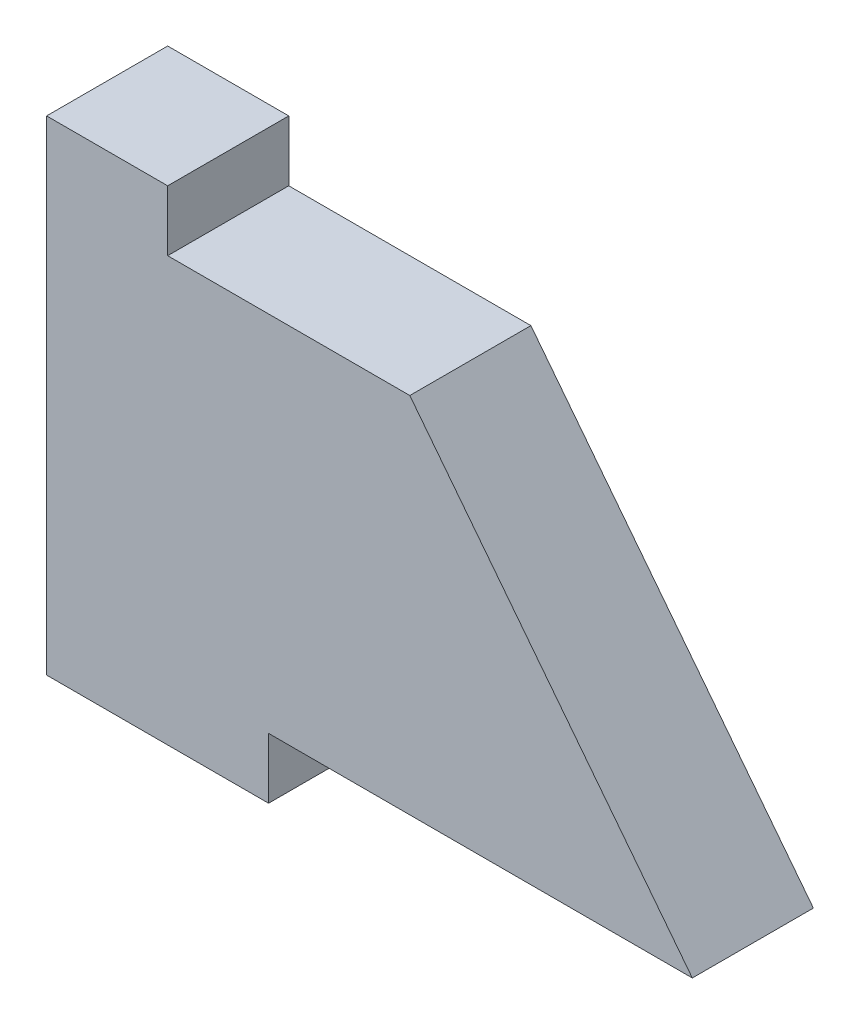
SolidWorks part; units mm, degrees
ref_plane "Спереди" through (0, 0, 0) normal (0, 0, 1) x (1, 0, 0)
ref_plane "Сверху" through (0, 0, 0) normal (0, 1, 0) x (1, 0, 0)
ref_plane "Справа" through (0, 0, 0) normal (1, 0, 0) x (0, 0, -1)
sketch "Эскиз1" plane through (0, 0, 0) normal (0, 0, 1) x (1, 0, 0)
  line L0 (0, 9) -> (0, 0)
  line L1 (0, 0) -> (16, 0)
  line L2 (16, 0) -> (9, 9)
  line L3 (9, 9) -> (0, 9)
  dimension "D1" = 9
  dimension "D2" = 9
  dimension "D3" = 16
extrude "Бобышка-Вытянуть1" add sketch "Эскиз1" along normal blind 3
sketch "Эскиз2" plane through (0, 9, 0) normal (0, 1, 0) x (1, 0, 0)
  line L0 (0, -3) -> (0, 0) construction
  line L1 (0, 0) -> (3, 0)
  line L2 (0, 0) -> (0, -3)
  line L3 (0, -3) -> (3, -3)
  line L4 (3, 0) -> (3, -3)
  line L7 (9, -3) -> (0, -3) construction
  line L8 (9, 0) -> (0, 0) construction
  point P6 (3, -3)
  point P9 (3, 0)
  dimension "D1" = 3
extrude "Бобышка-Вытянуть2" add sketch "Эскиз2" along normal blind 1.5
sketch "Эскиз3" plane through (0, 0, 0) normal (0, -1, 0) x (1, 0, 0)
  line L0 (0, 3) -> (16, 3) construction
  line L1 (0, 0) -> (5.5, 0)
  line L2 (0, 0) -> (0, 3)
  line L3 (0, 3) -> (5.5, 3)
  line L4 (5.5, 0) -> (5.5, 3)
  dimension "D1" = 5.5
extrude "Бобышка-Вытянуть3" add sketch "Эскиз3" along normal blind 1.5
